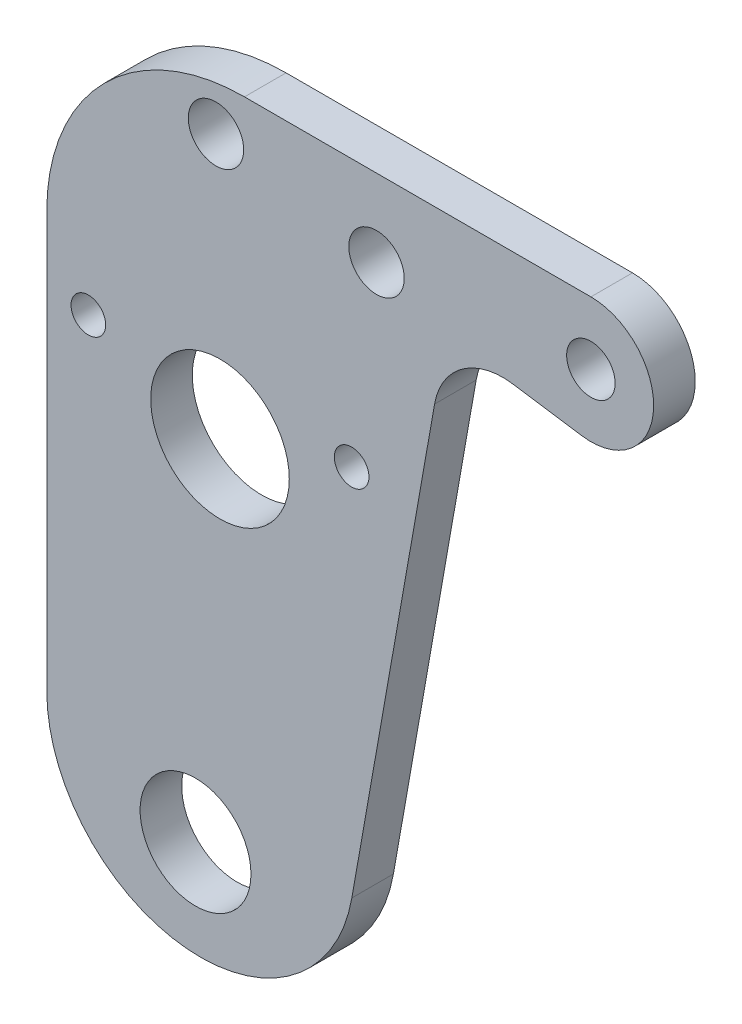
SolidWorks part; units mm, degrees
ref_plane "Front Plane" through (0, 0, 0) normal (0, 0, 1) x (1, 0, 0)
ref_plane "Top Plane" through (0, 0, 0) normal (0, 1, 0) x (1, 0, 0)
ref_plane "Right Plane" through (0, 0, 0) normal (1, 0, 0) x (0, 0, -1)
sketch "Sketch3" plane through (0, 0, 0) normal (0, 0, 1) x (1, 0, 0)
  line L0 (-12.5, -15) -> (-12.5, 15)
  line L1 (1.7668, 29.2668) -> (26.7668, 29.2668)
  line L2 (26.095, 20.2608) -> (21.1503, 21.0025)
  line L3 (15.4845, 16.9261) -> (9.5155, -16.9261)
  line L4 (-12.5, 0) -> (12.5, 0) construction
  line L5 (-2.3747, -26.0498) -> (-1.408, -15) construction
  arc A0 (-12.5, 15) -> (1.7668, 29.2668) centre (1.7668, 15) cw
  arc A1 (26.7668, 29.2668) -> (26.095, 20.2608) centre (26.7668, 24.7387) cw
  arc A2 (21.1503, 21.0025) -> (15.4845, 16.9261) centre (20.4086, 16.0579) ccw
  arc A3 (-12.5, -15) -> (9.5155, -16.9261) centre (-1.408, -15) ccw
  circle A4 centre (-1.7646, -19.0764) radius 4
  point P18 (-1.9862, -21.6085)
  dimension "D3" = 10
  dimension "D8" = 5
  dimension "D10" = 8
  dimension "D1" = 25
  dimension "D2" = 30
  dimension "D5" = 25
  dimension "D6" = 5
  dimension "D9" = 7
extrude "Boss-Extrude4" add sketch "Sketch3" along normal blind 3
sketch "Sketch5" plane through (0, 0, 3) normal (0, 0, 1) x (1, 0, 0)
  line L0 (-9.5, 10) -> (9.5, 10) construction
  line L1 (0, 10) -> (0, 7) construction
  line L2 (0, 7) -> (0, 0) construction
  circle A0 centre (-9.5, 10) radius 1.25
  circle A1 centre (9.5, 10) radius 1.25
  circle A2 centre (0, 7) radius 5
  dimension "D2" = 10
  dimension "D3" = 2.5
  dimension "D1" = 19
  dimension "D4" = 3
  dimension "D5" = 7
extrude "Cut-Extrude2" cut sketch "Sketch5" against normal through all
sketch "Sketch6" plane through (0, 0, 3) normal (0, 0, 1) x (1, 0, 0)
  circle A0 centre (26.7668, 24.7387) radius 1.75
  dimension "D1" = 3.5
extrude "Cut-Extrude3" cut sketch "Sketch6" against normal through all
sketch "Sketch8" plane through (0, 0, 3) normal (0, 0, 1) x (1, 0, 0)
  circle A0 centre (11.2954, 23.6809) radius 2 construction
  circle A1 centre (-0.2894, 25.9197) radius 2 construction
  circle A2 centre (11.2954, 23.6809) radius 2
  circle A3 centre (-0.2894, 25.9197) radius 2
extrude "Cut-Extrude4" cut sketch "Sketch8" against normal through all
